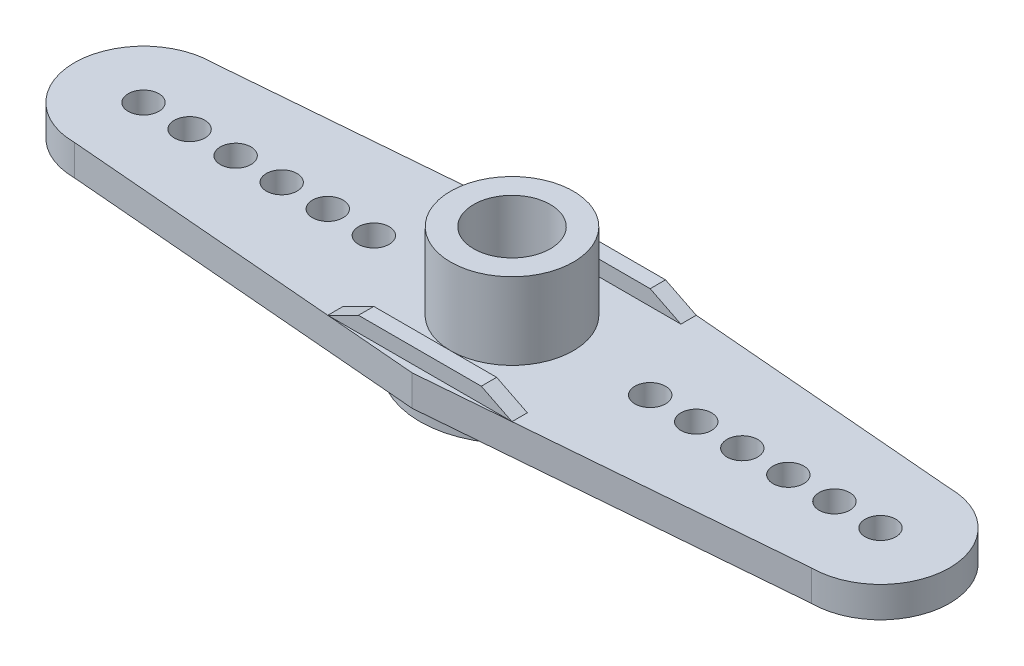
SolidWorks part; units mm, degrees
ref_plane "Front Plane" through (0, 0, 0) normal (0, 0, 1) x (1, 0, 0)
ref_plane "Top Plane" through (0, 0, 0) normal (0, 1, 0) x (1, 0, 0)
ref_plane "Right Plane" through (0, 0, 0) normal (1, 0, 0) x (0, 0, -1)
sketch "Sketch1" plane through (0, 0, 0) normal (0, 1, 0) x (1, 0, 0)
  line L0 (-28.5, 0) -> (28.5, 0) construction
  line L1 (-24, 4.5) -> (0, 6.5)
  line L2 (0, 6.5) -> (24, 4.5)
  line L3 (24, -4.5) -> (0, -6.5)
  line L4 (-24, -4.5) -> (0, -6.5)
  line L5 (0, 0) -> (0, 6.5) construction
  arc A0 (-24, 4.5) -> (-24, -4.5) centre (-24, 0) ccw
  arc A1 (24, -4.5) -> (24, 4.5) centre (24, 0) ccw
  circle A2 centre (0, 0) radius 6.5
  circle A3 centre (24, 0) radius 1
  circle A4 centre (21, 0) radius 1
  circle A5 centre (18, 0) radius 1
  circle A6 centre (15, 0) radius 1
  circle A7 centre (12, 0) radius 1
  circle A8 centre (9, 0) radius 1
  circle A9 centre (-24, 0) radius 1
  circle A10 centre (-21, 0) radius 1
  circle A11 centre (-18, 0) radius 1
  circle A12 centre (-15, 0) radius 1
  circle A13 centre (-12, 0) radius 1
  circle A14 centre (-9, 0) radius 1
  circle A15 centre (0, 0) radius 1.5
  point P6 (0, 0)
  dimension "D2" = 9
  dimension "D3" = 13
  dimension "D4" = 2
  dimension "D6" = 3
  dimension "D1" = 57
  dimension "D5" = 6
extrude "Boss-Extrude1" add sketch "Sketch1" along normal blind 2 contours A2 L1 A0 L4 A13 A11 A9 A10 A12 A14 | L3 A2 L2 L1 L4 A15 | A2 L3 A1 L2 A8 A7 A6 A5 A4 A3
sketch "Sketch2" plane through (0, 2, 0) normal (0, 1, 0) x (1, 0, 0)
  circle A0 centre (0, 0) radius 2.5
  circle A1 centre (0, 0) radius 4
  dimension "D1" = 5
  dimension "D2" = 1.5
extrude "Boss-Extrude2" add sketch "Sketch2" along normal blind 5
sketch "Sketch3" plane through (0, 0, 0) normal (0, -1, 0) x (1, 0, 0)
  circle A0 centre (0, 0) radius 4
  circle A1 centre (0, 0) radius 6
  dimension "D1" = 12
  dimension "D2" = 8
extrude "Boss-Extrude3" add sketch "Sketch3" along normal blind 1
sketch "Sketch4" plane through (0, 0, 0) normal (0, -1, 0) x (1, 0, 0)
  circle A0 centre (0, 0) radius 3.5
  dimension "D1" = 7
extrude "Cut-Extrude1" cut sketch "Sketch4" against normal blind 1
sketch "Sketch5" plane through (0, 2, 0) normal (0, 1, 0) x (1, 0, 0)
  line L0 (-24, 4.5) -> (0, 6.5) construction
  line L1 (-6, 6) -> (6, 6)
  line L2 (-6, 6) -> (-6, 5)
  line L3 (-6, 5) -> (6, 5)
  line L4 (6, 6) -> (6, 5)
  line L5 (0, 6.5) -> (24, 4.5) construction
  line L6 (0, 0) -> (4, 0) construction
  line L7 (6, -6) -> (6, -5)
  line L8 (-6, -6) -> (-6, -5)
  line L9 (-6, -6) -> (6, -6)
  line L10 (-6, -5) -> (6, -5)
  circle A0 centre (0, 0) radius 4 construction
  circle A1 centre (0, 0) radius 4 construction
  dimension "D1" = 12
  dimension "D2" = 1
extrude "Boss-Extrude4" add sketch "Sketch5" along normal blind 1
sketch "Sketch6" plane through (0, 0, 6) normal (0, 0, 1) x (1, 0, 0)
  line L0 (-4, 3) -> (-6, 2)
  line L1 (-6, 3) -> (6, 3) construction
  line L2 (-4, 7) -> (-4, 2) construction
  line L6 (6, 2) -> (4, 3)
  line L10 (-6, 2) -> (-6, 3)
  line L11 (-6, 3) -> (-4, 3)
  line L12 (4, 3) -> (6, 3)
  line L13 (6, 3) -> (6, 2)
  point P10 (6, 2)
extrude "Cut-Extrude2" cut sketch "Sketch6" against normal blind 20
